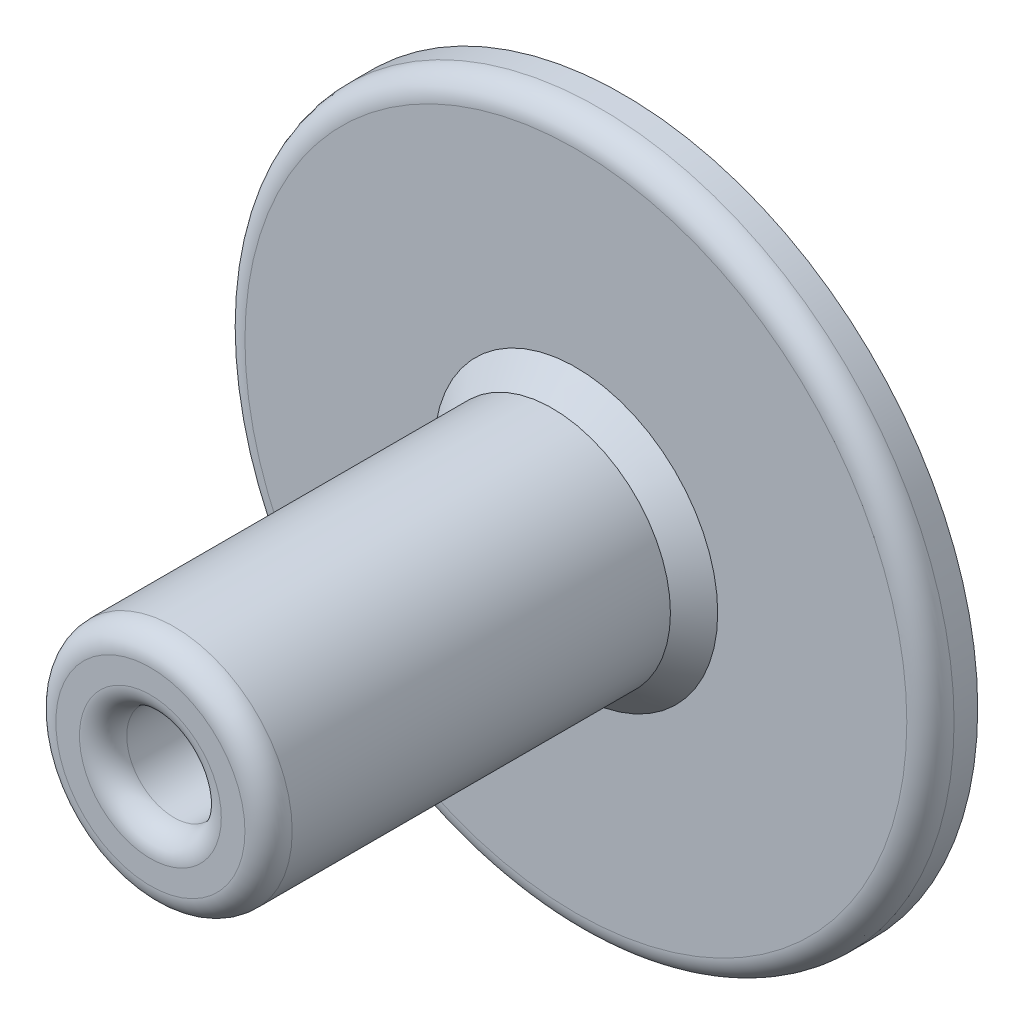
SolidWorks part; units mm, degrees
ref_plane "Front Plane" through (0, 0, 0) normal (0, 0, 1) x (1, 0, 0)
ref_plane "Top Plane" through (0, 0, 0) normal (0, 1, 0) x (1, 0, 0)
ref_plane "Right Plane" through (0, 0, 0) normal (1, 0, 0) x (0, 0, -1)
sketch "Sketch1" plane through (0, 0, 0) normal (0, 0, 1) x (1, 0, 0)
  circle A0 centre (0, 0) radius 15
  dimension "D1" = 30
extrude "Boss-Extrude1" add sketch "Sketch1" along normal blind 2 contours A0
sketch "Sketch2" plane through (0, 0, 2) normal (0, 0, 1) x (1, 0, 0)
  circle A0 centre (0, 0) radius 5
  dimension "D1" = 10
extrude "Boss-Extrude2" add sketch "Sketch2" along normal blind 18
sketch "Sketch3" plane through (0, 0, 0) normal (0, 0, -1) x (-1, 0, 0)
  ellipse E0 centre (0, 0) end of major axis (2.7, 0) minor radius 2.2
  dimension "D1" = 2.7
  dimension "D2" = 2.2
extrude "Cut-Extrude1" cut sketch "Sketch3" against normal blind 3
sketch "Sketch4" plane through (0, 0, 0) normal (0, 0, -1) x (-1, 0, 0)
  circle A0 centre (0, 0) radius 2
  dimension "D1" = 4
extrude "Cut-Extrude2" cut sketch "Sketch4" against normal blind 30
fillet "Fillet2" radius 1 1 edges at (-2.7, 0, 0)
chamfer "Chamfer1" distance 1 angle 45 1 edges at (5, 0, 2)
fillet "Fillet3" radius 1 1 edges at (15, 0, 2)
fillet "Fillet4" radius 1 1 edges at (5, 0, 20)
fillet "Fillet6" radius 1 1 edges at (2, 0, 20)
